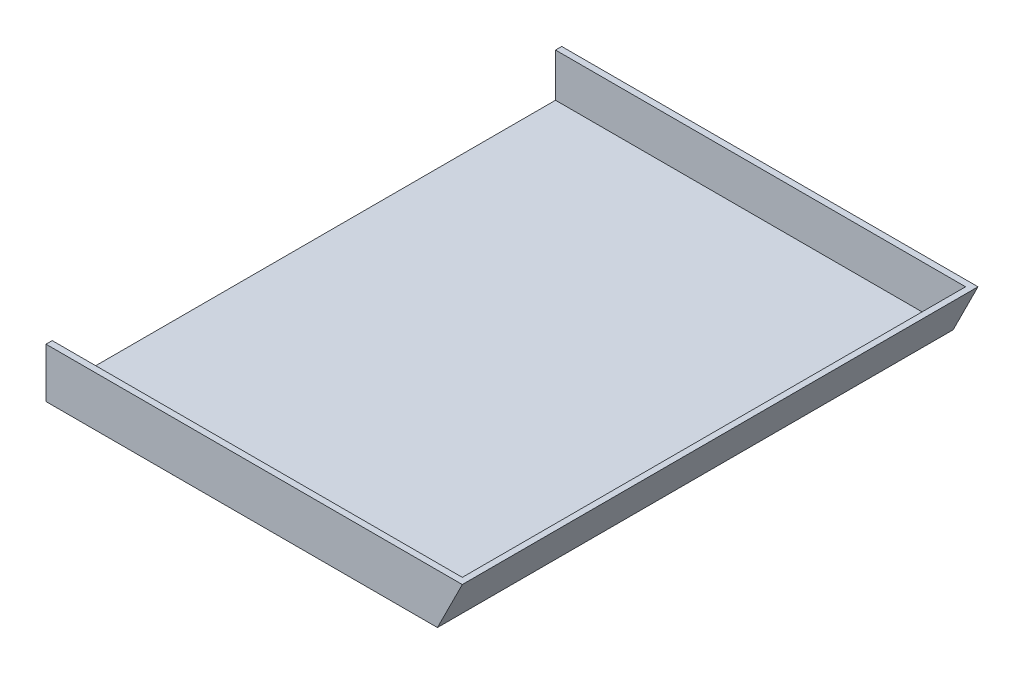
SolidWorks part; units mm, degrees
ref_plane "Спереди" through (0, 0, 0) normal (0, 0, 1) x (1, 0, 0)
ref_plane "Сверху" through (0, 0, 0) normal (0, 1, 0) x (1, 0, 0)
ref_plane "Справа" through (0, 0, 0) normal (1, 0, 0) x (0, 0, -1)
sketch "Эскиз2" plane through (0, 0, 0) normal (0, 0, 1) x (1, 0, 0)
  line L0 (29, 14.5) -> (32.5, 21.5)
  line L1 (-33.5, 21.5) -> (-33.5, 13.5) construction
  line L2 (-33.5, 14.5) -> (-33.5, 13.5)
  line L3 (-33.5, 13.5) -> (-3.4, 13.5)
  line L4 (-3.4, 0) -> (-3.4, 13.5)
  line L5 (-33.5, 21.5) -> (33.5, 13.5) construction
  line L6 (-33.5, 13.5) -> (33.5, 21.5) construction
  line L7 (-32.5, 20.5) -> (32.5, 20.5) construction
  line L8 (-32.5, 14.5) -> (29, 14.5)
  line L9 (33.5, 21.5) -> (32.5, 21.5)
  line L10 (-32.5, 14.5) -> (-33.5, 14.5)
  line L11 (32.5, 21.3806) -> (32.5, 21.5)
  line L12 (33.5, 21.5) -> (29.5, 13.5)
  line L13 (3.4, 13.5) -> (3.4, 0)
  line L14 (-33.5, 13.5) -> (33.5, 13.5) construction
  line L15 (33.5, 21.5) -> (33.5, 13.5) construction
  line L16 (-32.5, 14.5) -> (32.5, 14.5) construction
  line L17 (32.5, 20.5) -> (32.5, 14.5) construction
  line L18 (-33.5, 21.5) -> (33.5, 21.5) construction
  line L19 (-32.5, 20.5) -> (-32.5, 14.5) construction
  line L20 (3.4, 13.5) -> (29.5, 13.5)
  circle A0 centre (0, 0) radius 1.5
  arc A1 (-3.4, 0) -> (3.4, 0) centre (0, 0) ccw
  point P4 (0, 17.5)
  point P13 (29.5, 13.5)
  point P16 (28.5, 13.5)
  point P18 (0, 13.5)
  point P19 (0, 3.4)
  point P20 (33.5, 21.5)
  point P23 (0, 1.5)
  point P24 (0, 0)
  point P25 (-3.4, 0)
  point P26 (3.4, 0)
  dimension "D1" = 3
  dimension "D2" = 6.8
  dimension "D3" = 67
  dimension "D4" = 0
  dimension "D5" = 8
  dimension "D7" = 4
  dimension "D8" = 1
  dimension "D9" = 12
  dimension "D6" = 1
extrude "Бобышка-Вытянуть1" add sketch "Эскиз2" along normal blind 83
sketch "Эскиз3" plane through (0, 14.5, 0) normal (0, 1, 0) x (1, 0, 0)
  line L0 (-33.5, 0) -> (33.5, 0)
  line L1 (-33.5, -83) -> (33.5, -83)
  line L2 (-33.5, -1) -> (33.5, -1)
  line L3 (-33.5, -82) -> (33.5, -82)
  line L4 (-33.5, -83) -> (-33.5, -82)
  line L5 (33.5, -83) -> (33.5, -82)
  line L6 (-33.5, 0) -> (-33.5, -1)
  line L7 (-33.5, -1) -> (-33.4714, -1.0187)
  line L8 (33.5, -1) -> (33.5, 0)
  line M4 (-33.5, 0) -> (-33.5, -83)
  line M5 (-33.5, -83) -> (29, -83)
  line M6 (29, -83) -> (29, 0)
  dimension "D1" = 1
  dimension "D2" = 1
extrude "Бобышка-Вытянуть2" add sketch "Эскиз3" along normal blind 7 contours L3 M4 M5 M6 | L1 L5 L3 M6 | L2 L8 L0 L6
sketch "Эскиз4" plane through (0, 0, 83) normal (0, 0, 1) x (1, 0, 0)
  line L0 (29.5, 13.5) -> (33.5, 21.5)
  line L1 (33.5, 21.5) -> (33.5, 14.5)
  line L2 (33.5, 14.5) -> (29.5, 13.5)
extrude "Вырез-Вытянуть1" cut sketch "Эскиз4" against normal blind 83
sketch "Эскиз5" plane through (0, 0, 83) normal (0, 0, 1) x (1, 0, 0)
  line L1 (-3.4, 13.5) -> (3.4, 13.5)
  line L2 (-3.4, 13.5) -> (-3.4, -3.4)
  line L3 (-3.4, -3.4) -> (3.4, -3.4)
  line L4 (3.4, 13.5) -> (3.4, -3.4)
  arc A0 (-3.4, 0) -> (3.4, 0) centre (0, 0) ccw construction
  point P0 (3.4, 13.5)
  point P1 (3.4, 0)
  point P2 (0, -3.4)
extrude "Вырез-Вытянуть2" cut sketch "Эскиз5" against normal blind 79
sketch "Эскиз7" plane through (0, 0, 83) normal (0, 0, 1) x (1, 0, 0)
  line L0 (33.5, 21.5) -> (-33.5, 21.5) construction
  line L1 (3.4, 0) -> (3.4, 13.5) construction
  line L2 (3.4, 6.5) -> (-3.4, 6.5)
  line L3 (3.4, 6.5) -> (3.4, 13.5)
  line L4 (3.4, 13.5) -> (-3.4, 13.5)
  line L5 (-3.4, 6.5) -> (-3.4, 13.5)
  point P0 (0, 6.5)
  dimension "D1" = 15
extrude "Бобышка-Вытянуть3" add sketch "Эскиз7" against normal blind 38.5
sketch "Эскиз8" plane through (0, 0, 83) normal (0, 0, 1) x (1, 0, 0)
  line L1 (-3.4, 13.5) -> (3.4, 13.5)
  line L2 (-3.4, 13.5) -> (-3.4, 6.5)
  line L3 (-3.4, 6.5) -> (3.4, 6.5)
  line L4 (3.4, 13.5) -> (3.4, 6.5)
extrude "Вырез-Вытянуть3" cut sketch "Эскиз8" against normal blind 32
sketch "Эскиз9" plane through (0, 6.5, 0) normal (0, -1, 0) x (1, 0, 0)
  line L0 (3.4, 51) -> (-3.4, 44.5) construction
  line L1 (-3.4, 51) -> (3.4, 44.5) construction
  line L3 (-2.75, 49.1) -> (2.75, 49.1)
  line L4 (-2.75, 49.1) -> (-2.75, 46.4)
  line L5 (-2.75, 46.4) -> (2.75, 46.4)
  line L6 (2.75, 49.1) -> (2.75, 46.4)
  line L7 (-2.75, 49.1) -> (2.75, 46.4) construction
  line L8 (-2.75, 46.4) -> (2.75, 49.1) construction
  point P8 (0, 47.75)
  dimension "D1" = 2.7
  dimension "D2" = 5.5
extrude "Вырез-Вытянуть4" cut sketch "Эскиз9" against normal blind 7
